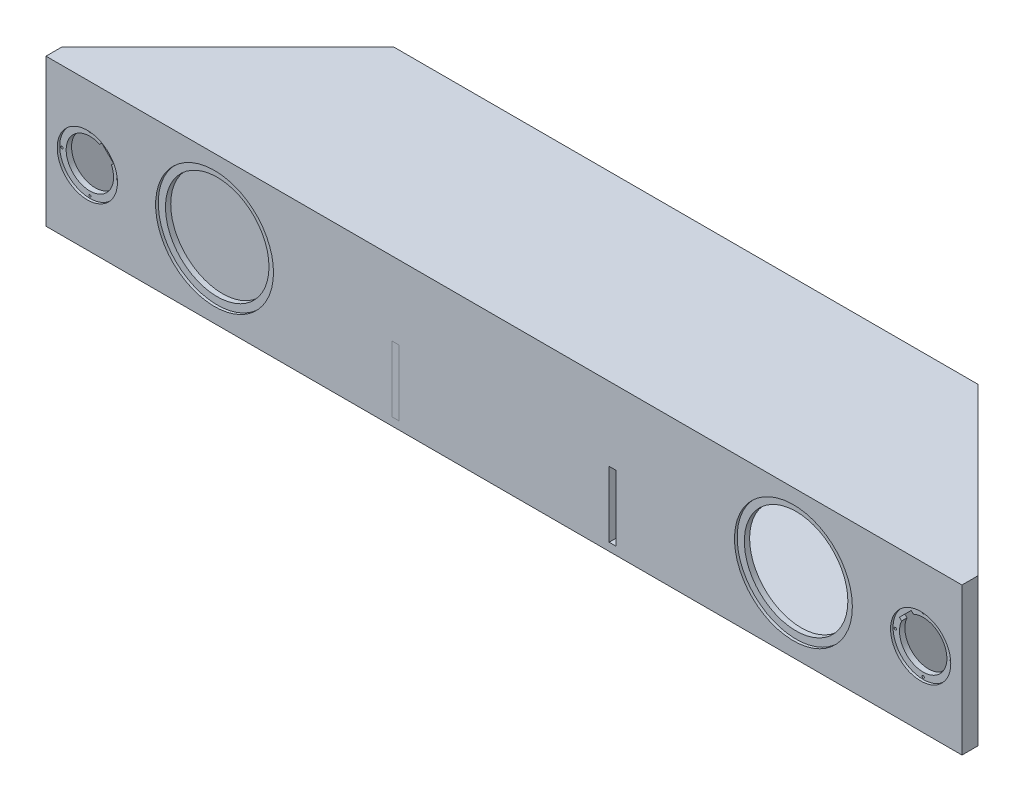
SolidWorks part; units mm, degrees
ref_plane "Front Plane" through (0, 0, 0) normal (0, 0, 1) x (1, 0, 0)
ref_plane "Top Plane" through (0, 0, 0) normal (0, 1, 0) x (1, 0, 0)
ref_plane "Right Plane" through (0, 0, 0) normal (1, 0, 0) x (0, 0, -1)
sketch "Sketch1" plane through (0, 0, 0) normal (0, 0, 1) x (1, 0, 0)
  line L1 (685.8, 110.3122) -> (-685.8, 110.3122)
  line L2 (685.8, 110.3122) -> (685.8, -110.3122)
  line L3 (685.8, -110.3122) -> (-685.8, -110.3122)
  line L4 (-685.8, 110.3122) -> (-685.8, -110.3122)
  line L5 (0, -110.3122) -> (0, 110.3122) construction
  line L6 (685.8, 0) -> (-685.8, 0) construction
  point P0 (0, 0)
  dimension "D1" = 1371.6
  dimension "D2" = 220.6244
extrude "Boss-Extrude1" add sketch "Sketch1" against normal blind 272.2372
sketch "Sketch3" plane through (0, 0, -272.2372) normal (0, 0, -1) x (-1, 0, 0)
  line L8 (673.9128, -98.425) -> (673.9128, 98.425)
  line L9 (673.9128, 98.425) -> (-673.9128, 98.425)
  line L10 (-673.9128, 98.425) -> (-673.9128, -98.425)
  line L11 (-673.9128, -98.425) -> (673.9128, -98.425)
  line L12 (673.9128, -98.425) -> (673.9128, 98.425)
  line L13 (673.9128, 98.425) -> (-673.9128, 98.425)
  line L14 (-673.9128, 98.425) -> (-673.9128, -98.425)
  line L15 (-673.9128, -98.425) -> (673.9128, -98.425)
  dimension "D1" = 11.8872
extrude "Cut-Extrude2" cut sketch "Sketch3" against normal offset from surface (260.35 mm away) 11.8872 up to face at (0, 0, 0)
sketch "Sketch4" plane through (0, 0, -11.8872) normal (0, 0, -1) x (-1, 0, 0)
  line L0 (0, 98.425) -> (0, -98.425) construction
  line L13 (673.9128, -98.425) -> (-673.9128, -98.425) construction
  line L14 (-573.9128, 98.425) -> (-562.0256, 98.425)
  line L19 (-573.9128, 98.425) -> (-573.9128, -98.425)
  line L20 (-573.9128, -98.425) -> (-562.0256, -98.425)
  line L21 (-673.9128, -98.425) -> (-673.9128, 98.425) construction
  line L23 (-673.9128, 98.425) -> (673.9128, 98.425) construction
  line L24 (-562.0256, 98.425) -> (-562.0256, -98.425)
  line L26 (573.9128, 98.425) -> (562.0256, 98.425)
  line L27 (573.9128, 98.425) -> (573.9128, -98.425)
  line L28 (573.9128, -98.425) -> (562.0256, -98.425)
  line L29 (562.0256, 98.425) -> (562.0256, -98.425)
  point P10 (0, 0)
  point P11 (-556.1942, -98.425)
  point P14 (-578.6633, -98.425)
  point P15 (0, 98.425)
  point P16 (0, -98.425)
  point P18 (-555.7378, 98.425)
  point P19 (0, 0)
  point P20 (562.0256, 98.425)
  point P21 (0, 0)
  point P25 (573.9128, -98.425)
  point P26 (-562.0256, 98.425)
  dimension "D1" = 11.8872
  dimension "D2" = 100
extrude "Boss-Extrude4" add sketch "Sketch4" along normal up to surface (260.35 mm away) up to face at (0, 0, -272.2372)
sketch "Sketch23" plane through (0, 110.3122, 0) normal (0, 1, 0) x (1, 0, 0)
  line L0 (-685.8, 24) -> (-437.5628, 272.2372)
  line L1 (-685.8, 272.2372) -> (-685.8, 0) construction
  line L2 (685.8, 0) -> (-685.8, 0) construction
  line L3 (-437.5628, 272.2372) -> (-685.8, 272.2372)
  line L4 (-685.8, 272.2372) -> (-685.8, 24)
  line L5 (0, 0) -> (0, 272.2372) construction
  line L6 (685.8, 272.2372) -> (-685.8, 272.2372) construction
  line L7 (685.8, 272.2372) -> (685.8, 24)
  line L8 (437.5628, 272.2372) -> (685.8, 272.2372)
  line L9 (685.8, 24) -> (437.5628, 272.2372)
  dimension "D1" = 24
  dimension "D2" = 45
extrude "Cut-Extrude3" cut sketch "Sketch23" against normal through all both and the other way through all
sketch "Sketch5" plane through (0, 0, -11.8872) normal (0, 0, -1) x (-1, 0, 0)
  line L0 (673.9128, 98.425) -> (573.9128, 98.425) construction
  line L1 (167.6384, 98.425) -> (179.5256, 98.425)
  line L2 (167.6384, 98.425) -> (167.6384, -98.425)
  line L3 (167.6384, -98.425) -> (179.5256, -98.425)
  line L4 (179.5256, 98.425) -> (179.5256, -98.425)
  line L5 (-673.9128, -98.425) -> (-573.9128, -98.425) construction
  line L6 (562.0256, 98.425) -> (562.0256, -98.425) construction
  line L7 (-167.6384, 98.425) -> (-179.5256, 98.425)
  line L8 (-167.6384, 98.425) -> (-167.6384, -98.425)
  line L9 (-167.6384, -98.425) -> (-179.5256, -98.425)
  line L10 (-179.5256, 98.425) -> (-179.5256, -98.425)
  line L11 (-562.0256, 98.425) -> (562.0256, 98.425) construction
  line L12 (0, 98.425) -> (0, -98.425) construction
  line L13 (437.5628, 98.425) -> (-437.5628, 98.425) construction
  line L14 (-437.5628, -98.425) -> (437.5628, -98.425) construction
  line L15 (-437.5628, -98.425) -> (437.5628, -98.425) construction
  line L16 (-5.9436, 98.425) -> (5.9436, 98.425)
  line L17 (-5.9436, 98.425) -> (-5.9436, -98.425)
  line L18 (-5.9436, -98.425) -> (5.9436, -98.425)
  line L19 (5.9436, 98.425) -> (5.9436, -98.425)
  dimension "D1" = 11.8872
  dimension "D2" = 382.5
extrude "INTERNAL BRACING" add sketch "Sketch5" along normal up to surface (260.35 mm away) up to face at (0, 104.3686, -272.2372)
sketch "Sketch2" plane through (0, 0, 0) normal (0, 0, 1) x (1, 0, 0)
  line L0 (433.4128, 0) -> (-433.4128, 0) construction
  line L1 (433.4128, -98.425) -> (433.4128, 0) construction
  line L2 (685.8, -110.3122) -> (685.8, 110.3122) construction
  line L3 (623.9128, 0) -> (685.8, 0) construction
  line L5 (0, 0) -> (0, 110.3122) construction
  line L6 (685.8, 110.3122) -> (-685.8, 110.3122) construction
  line L7 (623.9128, 0) -> (623.9128, 98.425) construction
  line L9 (573.9128, 98.425) -> (673.9128, 98.425) construction
  circle A0 centre (433.4128, 0) radius 77.5
  circle A1 centre (623.9128, 0) radius 45.1
  circle A2 centre (-433.4128, 0) radius 77.5
  circle A3 centre (-623.9128, 0) radius 45.1
  point P4 (0, 0)
  dimension "D1" = 155
  dimension "D2" = 90.2
  dimension "D3" = 190.5
extrude "Cut-Extrude1" cut sketch "Sketch2" against normal blind 14
sketch "Sketch128" plane through (0, 0, 0) normal (0, 0, 1) x (1, 0, 0)
  line L0 (0, 110.3122) -> (0, -110.3122) construction
  line L1 (685.8, 110.3122) -> (-685.8, 110.3122) construction
  line L2 (-685.8, -110.3122) -> (685.8, -110.3122) construction
  circle A0 centre (-623.9128, 0) radius 35.5
  circle A1 centre (623.9128, 0) radius 45.1
  circle A3 centre (-623.9128, 0) radius 45.1
  circle A4 centre (-623.9128, 0) radius 45.1
  circle A5 centre (623.9128, 0) radius 35.5
  dimension "D3" = 71
  dimension "D2" = 0
extrude "Boss-Extrude2" add sketch "Sketch128" against normal up to surface (8.0872 mm away) from offset 3.8 up to face at (86.791, 0, -11.8872) offset against normal yes
sketch "Sketch129" plane through (0, 0, -3.8) normal (0, 0, 1) x (1, 0, 0)
  line L0 (-588.3641, 17.8711) -> (-606.0417, 35.5487)
  line L1 (-588.3641, 17.8711) -> (-591.5793, 14.6558)
  line L2 (-606.0417, 35.5487) -> (-609.257, 32.3335)
  line L3 (-591.5793, 14.6558) -> (-609.257, 32.3335)
  line L4 (-588.3641, 17.8711) -> (-609.257, 32.3335) construction
  line L5 (-606.0417, 35.5487) -> (-591.5793, 14.6558) construction
  line L6 (-598.8105, 25.1023) -> (-623.9128, 0) construction
  line L7 (0, 110.3122) -> (0, -110.3122) construction
  line L8 (685.8, 110.3122) -> (-685.8, 110.3122) construction
  line L9 (-685.8, -110.3122) -> (685.8, -110.3122) construction
  line L10 (598.8105, 25.1023) -> (623.9128, 0) construction
  line L11 (606.0417, 35.5487) -> (591.5793, 14.6558) construction
  line L12 (588.3641, 17.8711) -> (609.257, 32.3335) construction
  line L13 (591.5793, 14.6558) -> (609.257, 32.3335)
  line L14 (606.0417, 35.5487) -> (609.257, 32.3335)
  line L15 (588.3641, 17.8711) -> (591.5793, 14.6558)
  line L16 (588.3641, 17.8711) -> (606.0417, 35.5487)
  circle A0 centre (-623.9128, 0) radius 35.5 construction
  point P1 (-598.8105, 25.1023)
  dimension "D1" = 45
  dimension "D2" = 25
extrude "Cut-Extrude4" cut sketch "Sketch129" against normal up to next
hole_wizard "M4x0.7 Tapped Hole1" positions "Sketch138" profile "Sketch139" tap size "M4x0.7" standard "ANSI Metric" end condition up to next
sketch "Sketch138" plane through (0, 0, -3.8) normal (0, 0, 1) x (1, 0, 0)
  line L0 (0, 110.3122) -> (0, -110.3122) construction
  line L1 (685.8, 110.3122) -> (-685.8, 110.3122) construction
  line L2 (-685.8, -110.3122) -> (685.8, -110.3122) construction
  circle A0 centre (-623.9128, 0) radius 41.75
  circle A1 centre (623.9128, 0) radius 41.75
  point P6 (-665.6628, 0)
  point P8 (-623.9128, 41.75)
  point P10 (-582.1628, 0)
  point P12 (-623.9128, -41.75)
  point P25 (623.9128, -41.75)
  point P26 (582.1628, 0)
  point P27 (623.9128, 41.75)
  point P28 (665.6628, 0)
  dimension "D1" = 83.5
sketch "Sketch139" plane through (665.6628, 0, -3.8) normal (1, 0, 0) x (0, -1, 0)
  line L0 (0, 0) -> (0, 8.0872)
  line L1 (0, 8.0872) -> (1.65, 8.0872)
  line L2 (1.65, 8.0872) -> (1.65, 0)
  line L5 (1.65, 0) -> (0, 0)
  line L11 (0, -6.35) -> (0, 107.95) construction
  dimension "Thru Tap Drill Dia." = 3.3
  dimension "Thru Tap Drill Depth" = 8.0872
cosmetic thread "Hole Thread1" parameters "D2"=4
cosmetic thread "Hole Thread2" parameters "D2"=4
cosmetic thread "Hole Thread3" parameters "D2"=4
cosmetic thread "Hole Thread4" parameters "D2"=4
cosmetic thread "Hole Thread5" parameters "D2"=4
cosmetic thread "Hole Thread6" parameters "D2"=4
cosmetic thread "Hole Thread7" parameters "D2"=4
cosmetic thread "Hole Thread8" parameters "D2"=4
sketch "Sketch193" plane through (0, 0, 0) normal (0, 0, 1) x (1, 0, 0)
  circle A0 centre (-433.4128, 0) radius 88.25
  circle A1 centre (433.4128, 0) radius 88.25
  dimension "D1" = 176.5
extrude "Cut-Extrude6" cut sketch "Sketch193" against normal blind 4
sketch "Sketch196" plane through (0, 110.3122, 0) normal (0, 1, 0) x (1, 0, 0)
  line L0 (-432.639, 260.35) -> (-685.8, 7.189)
  line L4 (685.8, 7.189) -> (432.639, 260.35)
  line L5 (432.639, 260.35) -> (167.6384, 260.35)
  line L6 (-437.5628, 272.2372) -> (-685.8, 24)
  line L7 (-685.8, 24) -> (-685.8, 0)
  line L8 (-685.8, 0) -> (685.8, 0)
  line L9 (685.8, 0) -> (685.8, 24)
  line L10 (685.8, 24) -> (437.5628, 272.2372)
  line L11 (437.5628, 272.2372) -> (-437.5628, 272.2372)
  line L12 (-437.5628, 272.2372) -> (-685.8, 24)
  line L13 (-685.8, 7.189) -> (-685.8, 24)
  line L15 (685.8, 24) -> (685.8, 7.189)
  line L16 (685.8, 24) -> (437.5628, 272.2372)
  line L17 (437.5628, 272.2372) -> (167.6384, 272.2372)
  line L18 (-685.8, 24) -> (-685.8, 0) construction
  line L19 (-432.639, 260.35) -> (-673.9128, 19.0762) construction
  line L20 (-673.9128, 19.0762) -> (-673.9128, 11.8872) construction
  line L21 (-673.9128, 11.8872) -> (673.9128, 11.8872) construction
  line L22 (-685.8, 0) -> (685.8, 0) construction
  line L23 (685.8, 0) -> (685.8, 24) construction
  line L24 (673.9128, 19.0762) -> (432.639, 260.35) construction
  line L25 (673.9128, 11.8872) -> (673.9128, 19.0762) construction
  line L26 (-167.6384, 272.2372) -> (-167.6384, 260.35)
  line L27 (167.6384, 272.2372) -> (167.6384, 260.35)
  line L28 (-167.6384, 272.2372) -> (-437.5628, 272.2372)
  line L29 (437.5628, 272.2372) -> (-437.5628, 272.2372) construction
  line L30 (-167.6384, 260.35) -> (-432.639, 260.35)
  line L31 (432.639, 260.35) -> (-432.639, 260.35) construction
  dimension "D1" = 0
  dimension "D2" = 11.8872
extrude "Boss-Extrude7" add sketch "Sketch196" against normal blind 220.6244
sketch "Sketch197" plane through (0, -98.425, 0) normal (0, 1, 0) x (1, 0, 0)
  line L0 (-167.6384, 272.2372) -> (-167.6384, 11.8872) construction
  line L5 (-432.639, 260.35) -> (-179.5256, 260.35) construction
  line L12 (0, 0) -> (0, 272.2372) construction
  line L13 (-437.5628, 272.2372) -> (437.5628, 272.2372) construction
  line L16 (-145.5912, 260.35) -> (-167.6384, 260.35)
  line L18 (-145.5912, 272.2372) -> (-167.6384, 272.2372)
  line L19 (-167.6384, 260.35) -> (-167.6384, 272.2372)
  line L28 (-5.9436, 11.8872) -> (-167.6384, 11.8872) construction
  line L43 (-145.5912, 260.35) -> (-145.5912, 11.8872)
  line L44 (-145.5912, 11.8872) -> (-157.4784, 11.8872)
  line L45 (-157.4784, 260.35) -> (-157.4784, 11.8872)
  line L47 (-145.5912, 272.2372) -> (-145.5912, 260.35)
  point P2 (-77.2408, 271.1507)
  point P3 (-75.5696, 272.2372)
  point P4 (-65.4096, 261.8705)
  dimension "D1" = 11.8872
extrude "Boss-Extrude11" add sketch "Sketch197" along normal through all and the other way up to surface other way up to face at (0, -110.3122, -98.7457)
sketch "Sketch198" plane through (0, -98.425, 0) normal (0, 1, 0) x (1, 0, 0)
  line L1 (-179.5256, 260.35) -> (-167.6384, 260.35)
  line L2 (-179.5256, 260.35) -> (-179.5256, 250.19)
  line L3 (-179.5256, 250.19) -> (-167.6384, 250.19)
  line L4 (-167.6384, 260.35) -> (-167.6384, 250.19)
  line L10 (685.8, 0) -> (-685.8, 0) construction
  line L15 (-157.4784, 11.8872) -> (-167.6384, 11.8872) construction
  line L16 (-157.4784, 11.8872) -> (-167.6384, 11.8872)
  line L17 (-157.4784, 11.8872) -> (-157.4784, 0)
  line L18 (-157.4784, 0) -> (-167.6384, 0)
  line L19 (-167.6384, 11.8872) -> (-167.6384, 0)
  line L20 (-167.6384, 260.35) -> (-157.4784, 260.35) construction
  line L21 (-157.4784, 11.8872) -> (-167.6384, 11.8872) construction
  line L22 (-179.5256, 260.35) -> (-179.5256, 11.8872) construction
  line L23 (-167.6384, 260.35) -> (-167.6384, 11.8872) construction
  point P4 (-284.3092, 272.2372)
  point P6 (-296.1964, 101.366)
  point P12 (-284.3092, 11.8872)
extrude "Cut-Extrude7" cut sketch "Sketch198" along normal blind 98.425
mirror "Mirror1" about plane through (0, 0, 0) normal (1, 0, 0) of "Cut-Extrude7", "Boss-Extrude11"
sketch "Sketch188" plane through (0, 0, -11.8872) normal (0, 0, -1) x (-1, 0, 0)
  line L4 (-673.9128, -98.425) -> (-573.9128, -98.425)
  line L5 (-573.9128, -98.425) -> (-573.9128, 98.425)
  line L6 (-573.9128, 98.425) -> (-673.9128, 98.425)
  line L7 (-673.9128, 98.425) -> (-673.9128, -98.425)
  line L8 (-673.9128, -98.425) -> (-573.9128, -98.425)
  line L9 (-573.9128, -98.425) -> (-573.9128, 98.425)
  line L10 (-573.9128, 98.425) -> (-673.9128, 98.425)
  line L11 (-673.9128, 98.425) -> (-673.9128, -98.425)
  dimension "D1" = 0
extrude "Boss-Extrude5" [suppressed] add sketch "Sketch188" along normal up to surface (260.35 mm away) separate body
sketch "Sketch199" plane through (0, -98.425, 0) normal (0, 1, 0) x (1, 0, 0)
  line L0 (-179.5256, 255.27) -> (-162.5584, 255.27) construction
  line L5 (-162.5584, 255.27) -> (-162.5584, 0) construction
  line L13 (-562.0256, 11.8872) -> (-179.5256, 11.8872)
  line L14 (-179.5256, 11.8872) -> (-179.5256, 250.19)
  line L15 (-179.5256, 250.19) -> (-167.6384, 250.19)
  line L17 (-167.6384, 250.19) -> (-167.6384, 0)
  line L19 (-167.6384, 0) -> (-157.4784, 0)
  line L20 (-157.4784, 0) -> (-157.4784, 260.35)
  line L21 (-157.4784, 260.35) -> (-432.639, 260.35)
  line L28 (-562.0256, 130.9634) -> (-562.0256, 11.8872)
  line L30 (-179.5256, 250.19) -> (-179.5256, 260.35)
  line L31 (-179.5256, 250.19) -> (-167.6384, 250.19)
  line L32 (-167.6384, 250.19) -> (-167.6384, 0)
  line L82 (-167.6384, 0) -> (-157.4784, 0)
  line L83 (-157.4784, 0) -> (-157.4784, 260.35)
  line L84 (-157.4784, 260.35) -> (-179.5256, 260.35)
  line L89 (-432.639, 260.35) -> (-562.0256, 130.9634)
  dimension "D1" = 0
extrude "Boss-Extrude12" add sketch "Sketch199" along normal up to surface (98.425 mm away) separate body up to face at (-162.5584, 0, -5.9436)
sketch "Sketch200" plane through (0, -98.425, 0) normal (0, 1, 0) x (1, 0, 0)
  line L21 (-179.5256, 11.8872) -> (-179.5256, 250.19)
  line L22 (-179.5256, 250.19) -> (-167.6384, 250.19)
  line L23 (-167.6384, 250.19) -> (-167.6384, 0)
  line L24 (-167.6384, 0) -> (-157.4784, 0)
  line L25 (-157.4784, 0) -> (-157.4784, 260.35)
  line L26 (-157.4784, 260.35) -> (-432.639, 260.35)
  line L27 (-432.639, 260.35) -> (-562.0256, 130.9634)
  line L28 (-562.0256, 130.9634) -> (-562.0256, 11.8872)
  line L29 (-562.0256, 11.8872) -> (-179.5256, 11.8872)
  line L30 (-179.5256, 11.8872) -> (-179.5256, 260.35)
  line L35 (-179.5256, 260.35) -> (-432.639, 260.35)
  line L36 (-432.639, 260.35) -> (-562.0256, 130.9634)
  line L37 (-562.0256, 130.9634) -> (-562.0256, 11.8872)
  line L38 (-562.0256, 11.8872) -> (-179.5256, 11.8872)
  dimension "D1" = 0
extrude "Boss-Extrude13" add sketch "Sketch200" along normal up to next separate body
